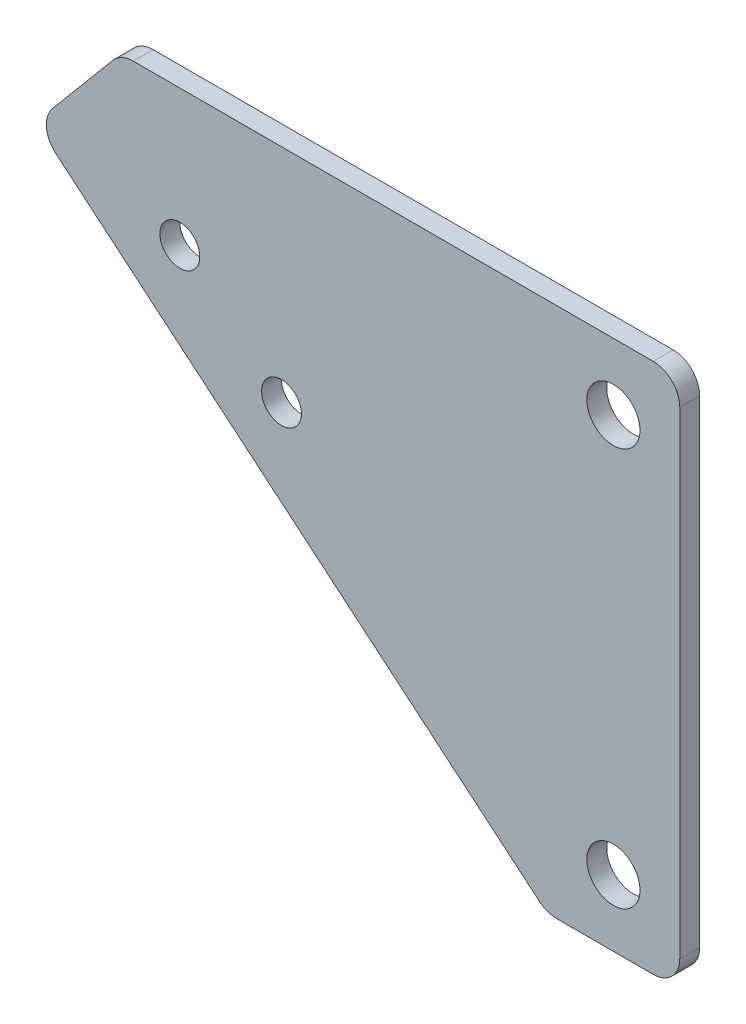
SolidWorks part; units mm, degrees
material "5052-H34"
ref_plane "正面" through (0, 0, 0) normal (0, 0, 1) x (1, 0, 0)
ref_plane "平面" through (0, 0, 0) normal (0, 1, 0) x (1, 0, 0)
ref_plane "右側面" through (0, 0, 0) normal (1, 0, 0) x (0, 0, -1)
sketch "ｽｹｯﾁ1" plane through (0, 0, 0) normal (0, 0, 1) x (1, 0, 0)
  line L0 (0, 0) -> (-10, 0)
  line L1 (-10, 0) -> (-48.5408, 32.3396)
  line L2 (-48.5408, 32.3396) -> (-42.1129, 40)
  line L3 (-42.1129, 40) -> (0, 40)
  line L4 (0, 40) -> (0, 0)
  line L5 (-5, 0) -> (-5, 40) construction
  line L6 (-45.3268, 36.1698) -> (-5, 2.3315) construction
  circle A0 centre (-37.6664, 29.7419) radius 1.5
  circle A1 centre (-30.006, 23.314) radius 1.5
  circle A2 centre (-5, 5) radius 2
  circle A3 centre (-5, 35) radius 2
  dimension "D4" = 3
  dimension "D5" = 10
  dimension "D6" = 10
  dimension "D7" = 4
  dimension "D8" = 5
  dimension "D9" = 5
  dimension "D1" = 10
  dimension "D2" = 40
  dimension "D3" = 140
extrude "ﾎﾞｽ - 押し出し1" add sketch "ｽｹｯﾁ1" along normal blind 1.5
fillet "ﾌｨﾚｯﾄ1" radius 2 5 edges at (-48.5408, 32.3396, 0.75) (-10, 0, 0.75) (0, 0, 0.75) (0, 40, 0.75) (-42.1129, 40, 0.75)
